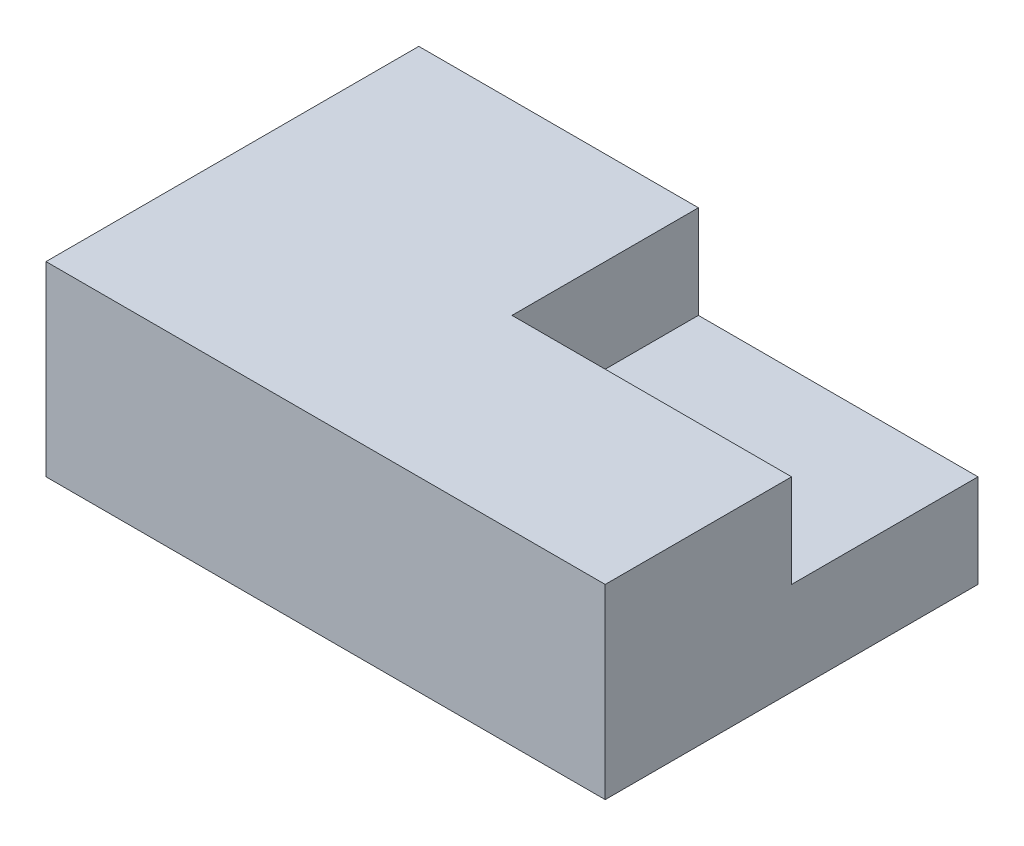
SolidWorks part; units mm, degrees
ref_plane "前视基准面" through (0, 0, 0) normal (0, 0, 1) x (1, 0, 0)
ref_plane "上视基准面" through (0, 0, 0) normal (0, 1, 0) x (1, 0, 0)
ref_plane "右视基准面" through (0, 0, 0) normal (1, 0, 0) x (0, 0, -1)
other "Configuration Table"
sketch "草图1" plane through (0, 0, 0) normal (0, 1, 0) x (1, 0, 0)
  line L1 (-15, 10) -> (15, 10)
  line L2 (-15, 10) -> (-15, -10)
  line L3 (-15, -10) -> (15, -10)
  line L4 (15, 10) -> (15, -10)
  line L5 (-15, 10) -> (15, -10) construction
  line L6 (-15, -10) -> (15, 10) construction
  point P0 (0, 0)
  dimension "D1" = 30
  dimension "D2" = 20
extrude "凸台-拉伸1" add sketch "草图1" along normal mid plane 10
sketch "草图2" plane through (0, 0, 0) normal (0, 1, 0) x (1, 0, 0)
  line L5 (15, 10) -> (0, 10)
  line L6 (15, 10) -> (15, 0)
  line L7 (15, 0) -> (0, 0)
  line L8 (0, 10) -> (0, 0)
extrude "切除-拉伸1" cut sketch "草图2" along normal through all
